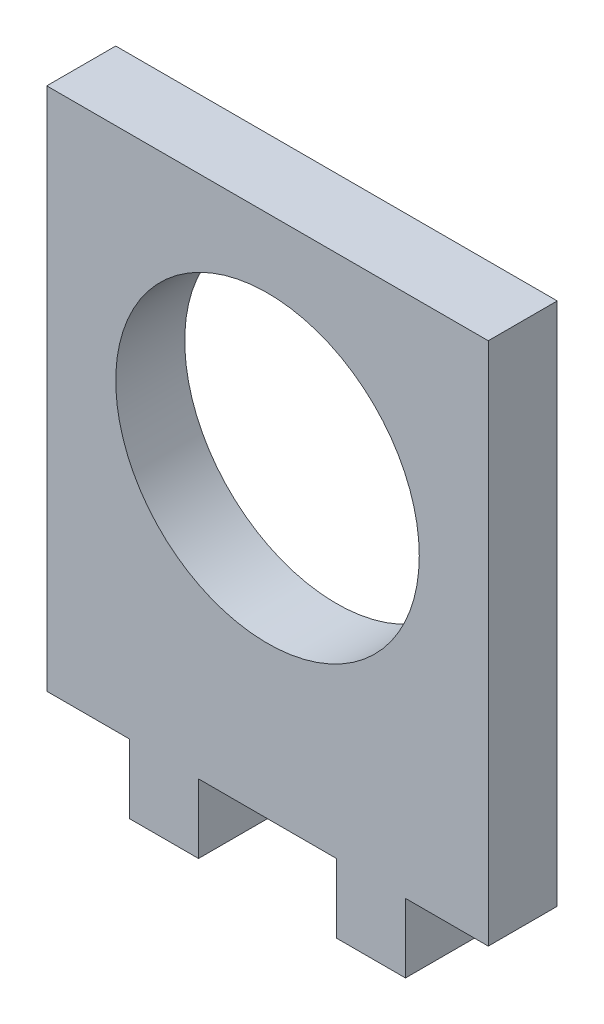
SolidWorks part; units mm, degrees
ref_plane "Front Plane" through (0, 0, 0) normal (0, 0, 1) x (1, 0, 0)
ref_plane "Top Plane" through (0, 0, 0) normal (0, 1, 0) x (1, 0, 0)
ref_plane "Right Plane" through (0, 0, 0) normal (1, 0, 0) x (0, 0, -1)
sketch "Sketch1" plane through (0, 0, 0) normal (0, 0, 1) x (1, 0, 0)
  line L0 (0, 0) -> (0, 27.0948) construction
  line L1 (-16, -22) -> (16, -22)
  line L2 (-16, -22) -> (-16, 16)
  line L3 (-16, 16) -> (16, 16)
  line L4 (16, -22) -> (16, 16)
  line L5 (-16, -22) -> (16, 16) construction
  line L6 (-16, 16) -> (16, -22) construction
  line L7 (0, 0) -> (37.5377, 0) construction
  circle A0 centre (0, 0) radius 11
  point P3 (0, -3)
  point P9 (0, 0)
  line B0 (0, -22) -> (0, -10.7792) construction
  line B1 (0, -22) -> (-5, -22)
  line B2 (-5, -27) -> (-10, -27)
  line B3 (-10, -27) -> (-10, -22)
  line B4 (-5, -27) -> (-5, -22)
  line B5 (0, -22) -> (5, -22)
  line B6 (5, -22) -> (5, -27)
  line B7 (5, -27) -> (10, -27)
  line B8 (10, -27) -> (10, -22)
  dimension "D1" = 22
  dimension "D2" = 16
  dimension "D3" = 16
  dimension "D4" = 16
  dimension "D5" = 22
sketch_block_instance "Insert Plots ep 5mm uniquement-1"
sketch_block "Insert Plots ep 5mm uniquement" parameters "D1"=10, "D2"=5, "D3"=5
extrude "Boss-Extrude1" add sketch "Sketch1" along normal blind 5 contours B7 B8 L1 B6 | B2 B4 L1 B3 | L1 L4 L3 L2 A0
